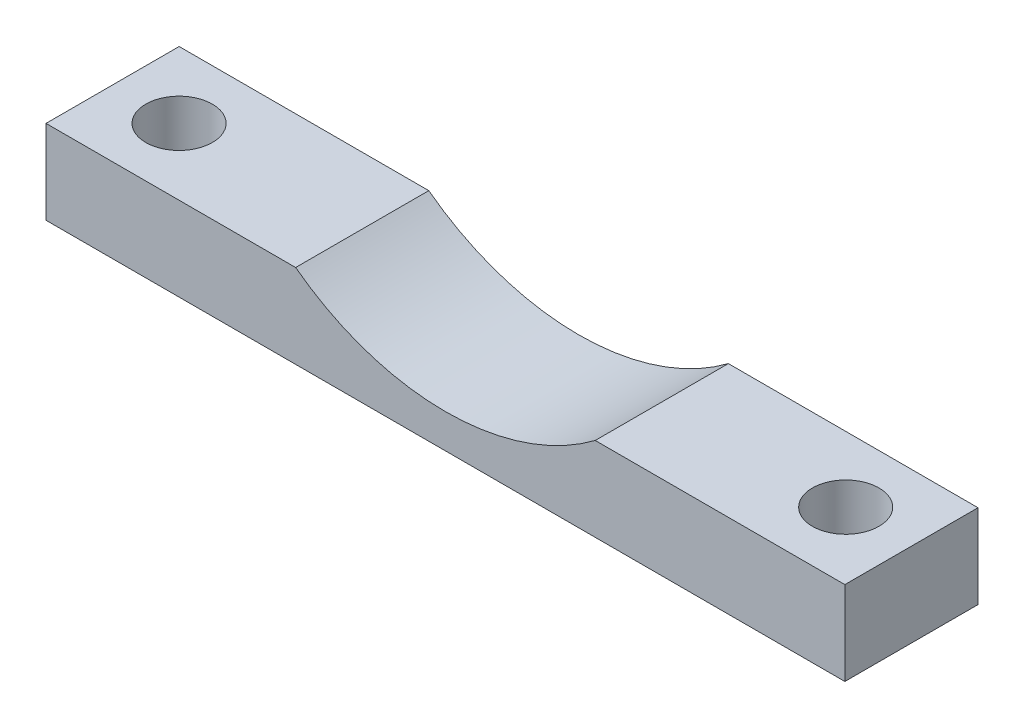
SolidWorks part; units mm, degrees
material "1060 Alloy"
ref_plane "Front Plane" through (0, 0, 0) normal (0, 0, 1) x (1, 0, 0)
ref_plane "Top Plane" through (0, 0, 0) normal (0, 1, 0) x (1, 0, 0)
ref_plane "Right Plane" through (0, 0, 0) normal (1, 0, 0) x (0, 0, -1)
sketch "Sketch1" plane through (0, 0, 0) normal (0, 0, 1) x (1, 0, 0)
  line L2 (0, 0) -> (0, 12.7) construction
  line L3 (0.0141, -19.0771) -> (0.0141, -15.2671) construction
  line L4 (0.0141, -15.2671) -> (-11.4159, -15.2671) construction
  line L6 (0.0141, -25.4271) -> (0.0141, -16.6463) construction
  line L7 (0.0141, -15.2671) -> (11.4441, -15.2671) construction
  line L8 (0.0141, -16.6463) -> (0.0141, -0.0271) construction
  line L9 (-11.4159, -15.2671) -> (-30.4659, -15.2671)
  line L11 (11.4441, -15.2671) -> (30.4941, -15.2671)
  line L14 (-30.4659, -15.2671) -> (-30.4659, -21.6713)
  line L15 (-30.4659, -21.6713) -> (30.4941, -21.6713)
  line L16 (30.4941, -21.6713) -> (30.4941, -15.2671)
  arc A2 (-11.4159, -15.2671) -> (11.4441, -15.2671) centre (0.0141, -0.0271) ccw
extrude "Boss-Extrude1" add sketch "Sketch1" along normal blind 10.16
sketch "Sketch2" plane through (0, -15.2671, 0) normal (0, 1, 0) x (1, 0, 0)
  line L0 (0.0141, -10.16) -> (0, 0) construction
  line L1 (-11.4159, -10.16) -> (11.4441, -10.16) construction
  line L2 (0.007, -5.08) -> (-25.393, -5.08) construction
  circle A0 centre (-25.393, -5.08) radius 2.54
  circle A1 centre (25.4069, -5.0095) radius 2.54
extrude "Cut-Extrude1" cut sketch "Sketch2" against normal through all
